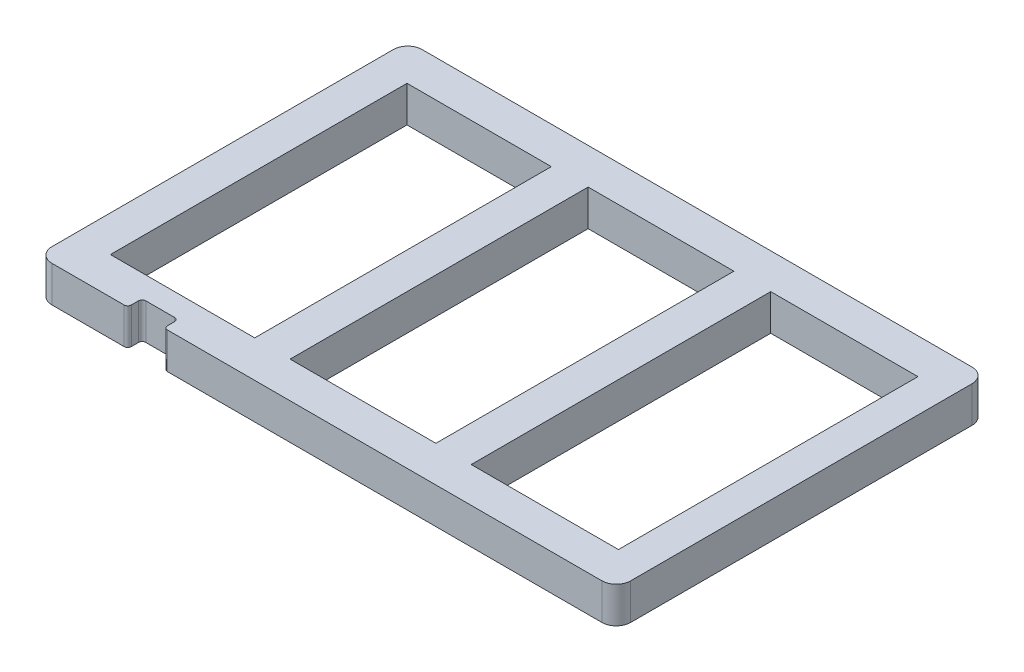
SolidWorks part; units mm, degrees
ref_plane "Front Plane" through (0, 0, 0) normal (0, 0, 1) x (1, 0, 0)
ref_plane "Top Plane" through (0, 0, 0) normal (0, 1, 0) x (1, 0, 0)
ref_plane "Right Plane" through (0, 0, 0) normal (1, 0, 0) x (0, 0, -1)
sketch "Sketch1" plane through (0, 0, 0) normal (0, 1, 0) x (1, 0, 0)
  line L0 (-2.5, -25.15) -> (-2.5, -24.15)
  line L1 (10, -20.55) -> (-10, -20.55)
  line L2 (10, -20.55) -> (10, 20.55)
  line L3 (10, 20.55) -> (-10, 20.55)
  line L4 (-10, -20.55) -> (-10, 20.55)
  line L5 (10, -20.55) -> (-10, 20.55) construction
  line L6 (10, 20.55) -> (-10, -20.55) construction
  line L7 (35.2, -20.65) -> (15, -20.65)
  line L8 (35.2, -20.65) -> (35.2, 20.65)
  line L9 (35.2, 20.65) -> (15, 20.65)
  line L10 (15, -20.65) -> (15, 20.65)
  line L11 (35.2, -20.65) -> (15, 20.65) construction
  line L12 (35.2, 20.65) -> (15, -20.65) construction
  line L13 (60.6, -20.75) -> (40.2, -20.75)
  line L14 (60.6, -20.75) -> (60.6, 20.75)
  line L15 (60.6, 20.75) -> (40.2, 20.75)
  line L16 (40.2, -20.75) -> (40.2, 20.75)
  line L17 (60.6, -20.75) -> (40.2, 20.75) construction
  line L18 (60.6, 20.75) -> (40.2, -20.75) construction
  line L19 (63.2, -25.65) -> (3, -25.65)
  line L20 (65.2, -23.65) -> (65.2, 23.65)
  line L21 (63.2, 25.65) -> (-13, 25.65)
  line L22 (-15, -23.65) -> (-15, 23.65)
  line L23 (65.2, -25.65) -> (-15, 25.65) construction
  line L24 (65.2, 25.65) -> (-15, -25.65) construction
  line L25 (-2, -23.65) -> (2, -23.65)
  line L26 (2.5, -24.15) -> (2.5, -25.15)
  line L27 (-3, -25.65) -> (-13, -25.65)
  arc A0 (2.5, -25.15) -> (3, -25.65) centre (3, -25.15) ccw
  arc A1 (2, -23.65) -> (2.5, -24.15) centre (2, -24.15) cw
  arc A2 (-2.5, -24.15) -> (-2, -23.65) centre (-2, -24.15) cw
  arc A3 (-2.5, -25.15) -> (-3, -25.65) centre (-3, -25.15) cw
  arc A4 (-13, 25.65) -> (-15, 23.65) centre (-13, 23.65) ccw
  arc A5 (65.2, 23.65) -> (63.2, 25.65) centre (63.2, 23.65) ccw
  arc A6 (63.2, -25.65) -> (65.2, -23.65) centre (63.2, -23.65) ccw
  arc A7 (-13, -25.65) -> (-15, -23.65) centre (-13, -23.65) cw
  point P0 (0, 0)
  point P6 (25.1, 0)
  point P11 (50.4, 0)
  point P16 (25.1, 0)
  point P25 (0, -23.65)
  point P28 (2.5, -25.65)
  point P31 (2.5, -23.65)
  point P34 (-2.5, -23.65)
  point P37 (-2.5, -25.65)
  dimension "D13" = 0.5
  dimension "D14" = 2
  dimension "D1" = 41.1
  dimension "D2" = 20
  dimension "D3" = 20.2
  dimension "D4" = 20.4
  dimension "D5" = 41.3
  dimension "D6" = 41.5
  dimension "D7" = 5
  dimension "D8" = 5
  dimension "D9" = 5
  dimension "D10" = 5
  dimension "D11" = 2
  dimension "D12" = 5
extrude "Boss-Extrude1" add sketch "Sketch1" along normal blind 5
